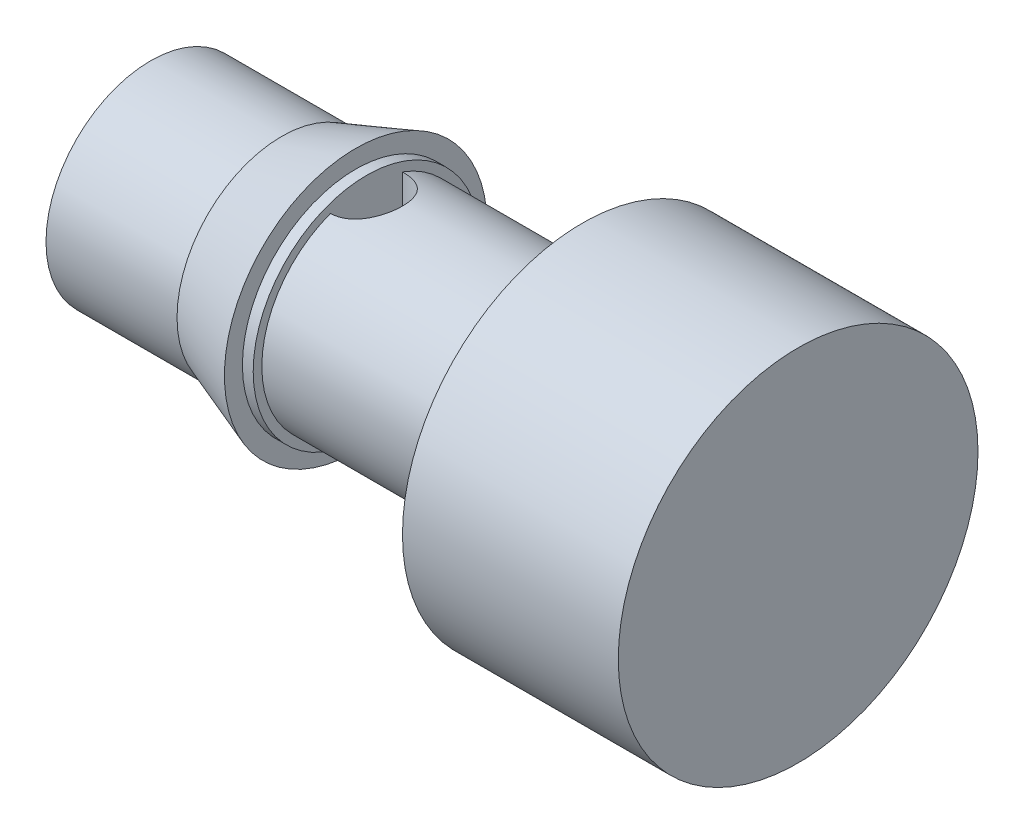
SolidWorks part; units mm, degrees
ref_plane "Front Plane" through (0, 0, 0) normal (0, 0, 1) x (1, 0, 0)
ref_plane "Top Plane" through (0, 0, 0) normal (0, 1, 0) x (1, 0, 0)
ref_plane "Right Plane" through (0, 0, 0) normal (1, 0, 0) x (0, 0, -1)
sketch "Sketch2" plane through (0, 0, 0) normal (1, 0, 0) x (0, 0, -1)
  circle A0 centre (0, 0) radius 1.455
  dimension "D1" = 2.91
extrude "Boss-Extrude3" add sketch "Sketch2" along normal blind 6 contours A0
sketch "Sketch3" plane through (6, 0, 0) normal (1, 0, 0) x (0, 0, -1)
  circle A0 centre (0, 0) radius 2.5
  dimension "D1" = 5
extrude "Boss-Extrude4" add sketch "Sketch3" along normal blind 3
sketch "Sketch4" plane through (0, 0, 0) normal (0, 1, 0) x (1, 0, 0)
  circle A0 centre (3, 0) radius 0.5
  dimension "D1" = 1
  dimension "D2" = 3
extrude "Cut-Extrude1" cut sketch "Sketch4" against normal through all both and the other way through all
ref_plane "Plane1" through (3, 0, 0) normal (-1, 0, 0) x (0, 0, 1)
sketch "Sketch6" plane through (3, 0, 0) normal (-1, 0, 0) x (0, 0, 1)
  circle A0 centre (0, 0) radius 1.575
  dimension "D1" = 3.15
extrude "Boss-Extrude5" add sketch "Sketch6" along normal blind 0.15
sketch "Sketch7" plane through (0, 0, 0) normal (0, 0, 1) x (1, 0, 0)
  line L0 (2.85, 1.825) -> (0, 0.8)
  line L1 (0, 0.8) -> (2.85, 0.8)
  line L2 (2.85, 0.8) -> (2.85, 1.825)
  dimension "D1" = 0
  dimension "D2" = 0
  dimension "D3" = 0.25
  dimension "D4" = 0.8
  dimension "D5" = 0
ref_axis "Axis1" through (9.45, 0, 0) along (-1, 0, 0)
revolve "Revolve1" add sketch "Sketch7" angle 360 about axis through (9.45, 0, 0) along (-1, 0, 0)
